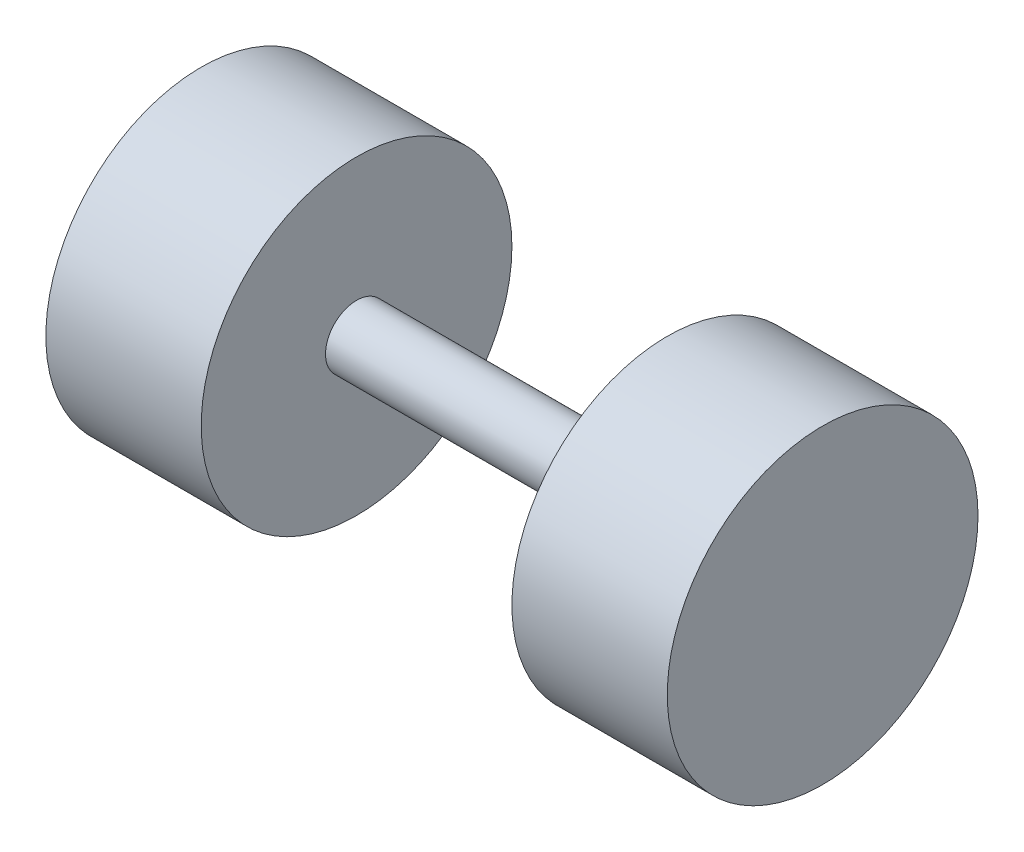
SolidWorks part; units mm, degrees
material "ﾊﾞﾙｻ"
ref_plane "正面" through (0, 0, 0) normal (0, 0, 1) x (1, 0, 0)
ref_plane "平面" through (0, 0, 0) normal (0, 1, 0) x (1, 0, 0)
ref_plane "右側面" through (0, 0, 0) normal (1, 0, 0) x (0, 0, -1)
sketch "ｽｹｯﾁ1" plane through (0, 0, 0) normal (0, 0, 1) x (1, 0, 0)
  line L1 (0, 0) -> (500, 0)
  line L2 (0, 0) -> (0, -500)
  line L3 (0, -500) -> (500, -500)
  line L4 (500, 0) -> (500, -500)
  line L5 (0, 0) -> (-500, 0)
  line L6 (0, 0) -> (0, -100)
  line L7 (0, -100) -> (-500, -100)
  line L8 (-500, 0) -> (-500, -100)
revolve "回転1" add sketch "ｽｹｯﾁ1" angle 360 about L5
mirror "ﾐﾗｰ1" about plane through (-500, 0, 0) normal (1, 0, 0) of bodies 101
